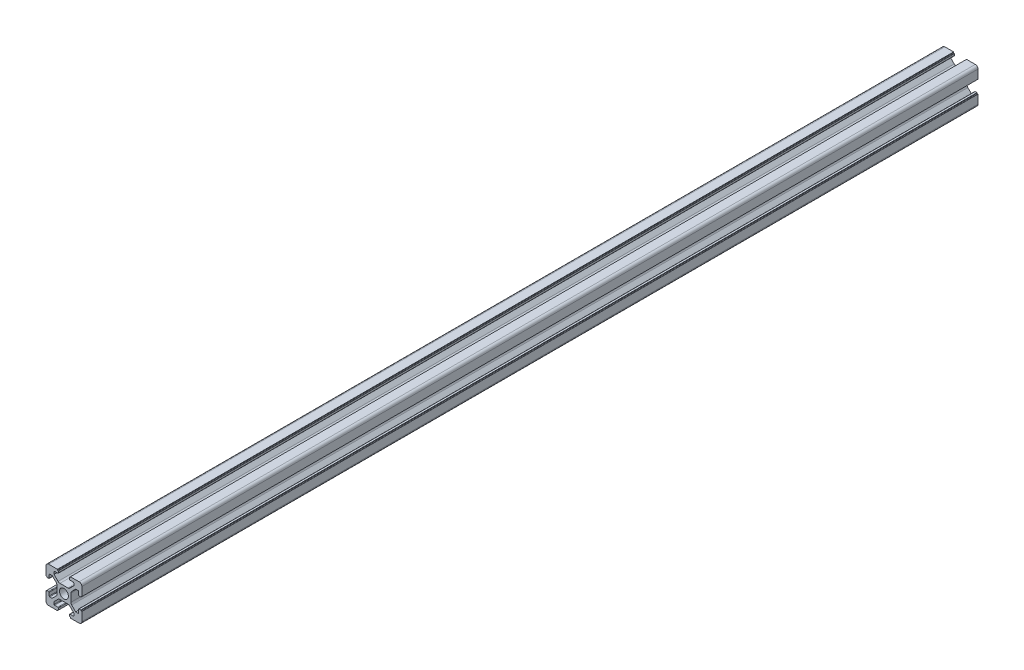
SolidWorks part; units mm, degrees
ref_plane "前视基准面" through (0, 0, 0) normal (0, 0, 1) x (1, 0, 0)
ref_plane "上视基准面" through (0, 0, 0) normal (0, 1, 0) x (1, 0, 0)
ref_plane "右视基准面" through (0, 0, 0) normal (1, 0, 0) x (0, 0, -1)
sketch "草图1" plane through (0, 0, 0) normal (0, 0, 1) x (1, 0, 0)
  line L0 (4.216, 3.2442) -> (6.4367, 5.4649)
  line L1 (6.4367, 5.4649) -> (7.7767, 5.4649)
  line L2 (8.0767, 5.1649) -> (8.0767, 3.3649)
  line L3 (8.3767, 3.0649) -> (9.3767, 3.0649)
  line L4 (9.3767, 3.0649) -> (9.3767, 3.3649)
  line L5 (9.5767, 3.5649) -> (9.8767, 3.5649)
  line L6 (9.8767, 3.5649) -> (9.8767, 8.4649)
  line L7 (8.3767, 9.9649) -> (3.4767, 9.9649)
  line L8 (3.4767, 9.9649) -> (3.4767, 9.6649)
  line L9 (3.2767, 9.4649) -> (2.9767, 9.4649)
  line L10 (2.9767, 9.4649) -> (2.9767, 8.4649)
  line L11 (3.2767, 8.1649) -> (5.0767, 8.1649)
  line L12 (5.3767, 7.8649) -> (5.3767, 6.5249)
  line L13 (5.3767, 6.5249) -> (3.156, 4.3042)
  line L14 (2.0953, 3.8649) -> (-2.342, 3.8649)
  line L15 (-3.4027, 4.3042) -> (-5.6233, 6.5249)
  line L16 (-5.6233, 6.5249) -> (-5.6233, 7.8649)
  line L17 (-5.3233, 8.1649) -> (-3.5233, 8.1649)
  line L18 (-3.2233, 8.4649) -> (-3.2233, 9.4649)
  line L19 (-3.2233, 9.4649) -> (-3.5233, 9.4649)
  line L20 (-3.7233, 9.6649) -> (-3.7233, 9.9649)
  line L21 (-3.7233, 9.9649) -> (-8.6233, 9.9649)
  line L22 (-10.1233, 8.4649) -> (-10.1233, 3.5649)
  line L23 (-10.1233, 3.5649) -> (-9.8233, 3.5649)
  line L24 (-9.6233, 3.3649) -> (-9.6233, 3.0649)
  line L25 (-9.6233, 3.0649) -> (-8.6233, 3.0649)
  line L26 (-8.3233, 3.3649) -> (-8.3233, 5.1649)
  line L27 (-8.0233, 5.4649) -> (-6.6833, 5.4649)
  line L28 (-6.6833, 5.4649) -> (-4.4627, 3.2442)
  line L29 (-4.0233, 2.1836) -> (-4.0233, -2.2538)
  line L30 (-4.4627, -3.3144) -> (-6.6833, -5.5351)
  line L31 (-6.6833, -5.5351) -> (-8.0233, -5.5351)
  line L32 (-8.3233, -5.2351) -> (-8.3233, -3.4351)
  line L33 (-8.6233, -3.1351) -> (-9.6233, -3.1351)
  line L34 (-9.6233, -3.1351) -> (-9.6233, -3.4351)
  line L35 (-9.8233, -3.6351) -> (-10.1233, -3.6351)
  line L36 (-10.1233, -3.6351) -> (-10.1233, -8.5351)
  line L37 (-8.6233, -10.0351) -> (-3.7233, -10.0351)
  line L38 (-3.7233, -10.0351) -> (-3.7233, -9.7351)
  line L39 (-3.5233, -9.5351) -> (-3.2233, -9.5351)
  line L40 (-3.2233, -9.5351) -> (-3.2233, -8.5351)
  line L41 (-3.5233, -8.2351) -> (-5.3233, -8.2351)
  line L42 (-5.6233, -7.9351) -> (-5.6233, -6.5951)
  line L43 (-5.6233, -6.5951) -> (-3.4027, -4.3744)
  line L44 (-2.342, -3.9351) -> (2.0953, -3.9351)
  line L45 (3.156, -4.3744) -> (5.3767, -6.5951)
  line L46 (5.3767, -6.5951) -> (5.3767, -7.9351)
  line L47 (5.0767, -8.2351) -> (3.2767, -8.2351)
  line L48 (2.9767, -8.5351) -> (2.9767, -9.5351)
  line L49 (2.9767, -9.5351) -> (3.2767, -9.5351)
  line L50 (3.4767, -9.7351) -> (3.4767, -10.0351)
  line L51 (3.4767, -10.0351) -> (8.3767, -10.0351)
  line L52 (9.8767, -8.5351) -> (9.8767, -3.6351)
  line L53 (9.8767, -3.6351) -> (9.5767, -3.6351)
  line L54 (9.3767, -3.4351) -> (9.3767, -3.1351)
  line L55 (9.3767, -3.1351) -> (8.3767, -3.1351)
  line L56 (8.0767, -3.4351) -> (8.0767, -5.2351)
  line L57 (7.7767, -5.5351) -> (6.4367, -5.5351)
  line L58 (6.4367, -5.5351) -> (4.216, -3.3144)
  line L59 (3.7767, -2.2538) -> (3.7767, 2.1836)
  circle A0 centre (-0.1233, -0.0351) radius 2.5
  arc A1 (8.0767, 5.1649) -> (7.7767, 5.4649) centre (7.7767, 5.1649) ccw
  arc A2 (8.0767, 3.3649) -> (8.3767, 3.0649) centre (8.3767, 3.3649) ccw
  arc A3 (9.5767, 3.5649) -> (9.3767, 3.3649) centre (9.5767, 3.3649) ccw
  arc A4 (9.8767, 8.4649) -> (8.3767, 9.9649) centre (8.3767, 8.4649) ccw
  arc A5 (3.2767, 9.4649) -> (3.4767, 9.6649) centre (3.2767, 9.6649) ccw
  arc A6 (2.9767, 8.4649) -> (3.2767, 8.1649) centre (3.2767, 8.4649) ccw
  arc A7 (5.3767, 7.8649) -> (5.0767, 8.1649) centre (5.0767, 7.8649) ccw
  arc A8 (2.0953, 3.8649) -> (3.156, 4.3042) centre (2.0953, 5.3649) ccw
  arc A9 (-3.4027, 4.3042) -> (-2.342, 3.8649) centre (-2.342, 5.3649) ccw
  arc A10 (-5.3233, 8.1649) -> (-5.6233, 7.8649) centre (-5.3233, 7.8649) ccw
  arc A11 (-3.5233, 8.1649) -> (-3.2233, 8.4649) centre (-3.5233, 8.4649) ccw
  arc A12 (-3.7233, 9.6649) -> (-3.5233, 9.4649) centre (-3.5233, 9.6649) ccw
  arc A13 (-8.6233, 9.9649) -> (-10.1233, 8.4649) centre (-8.6233, 8.4649) ccw
  arc A14 (-9.6233, 3.3649) -> (-9.8233, 3.5649) centre (-9.8233, 3.3649) ccw
  arc A15 (-8.6233, 3.0649) -> (-8.3233, 3.3649) centre (-8.6233, 3.3649) ccw
  arc A16 (-8.0233, 5.4649) -> (-8.3233, 5.1649) centre (-8.0233, 5.1649) ccw
  arc A17 (-4.0233, 2.1836) -> (-4.4627, 3.2442) centre (-5.5233, 2.1836) ccw
  arc A18 (-4.4627, -3.3144) -> (-4.0233, -2.2538) centre (-5.5233, -2.2538) ccw
  arc A19 (-8.3233, -5.2351) -> (-8.0233, -5.5351) centre (-8.0233, -5.2351) ccw
  arc A20 (-8.3233, -3.4351) -> (-8.6233, -3.1351) centre (-8.6233, -3.4351) ccw
  arc A21 (-9.8233, -3.6351) -> (-9.6233, -3.4351) centre (-9.8233, -3.4351) ccw
  arc A22 (-10.1233, -8.5351) -> (-8.6233, -10.0351) centre (-8.6233, -8.5351) ccw
  arc A23 (-3.5233, -9.5351) -> (-3.7233, -9.7351) centre (-3.5233, -9.7351) ccw
  arc A24 (-3.2233, -8.5351) -> (-3.5233, -8.2351) centre (-3.5233, -8.5351) ccw
  arc A25 (-5.6233, -7.9351) -> (-5.3233, -8.2351) centre (-5.3233, -7.9351) ccw
  arc A26 (-2.342, -3.9351) -> (-3.4027, -4.3744) centre (-2.342, -5.4351) ccw
  arc A27 (3.156, -4.3744) -> (2.0953, -3.9351) centre (2.0953, -5.4351) ccw
  arc A28 (5.0767, -8.2351) -> (5.3767, -7.9351) centre (5.0767, -7.9351) ccw
  arc A29 (3.2767, -8.2351) -> (2.9767, -8.5351) centre (3.2767, -8.5351) ccw
  arc A30 (3.4767, -9.7351) -> (3.2767, -9.5351) centre (3.2767, -9.7351) ccw
  arc A31 (8.3767, -10.0351) -> (9.8767, -8.5351) centre (8.3767, -8.5351) ccw
  arc A32 (9.3767, -3.4351) -> (9.5767, -3.6351) centre (9.5767, -3.4351) ccw
  arc A33 (8.3767, -3.1351) -> (8.0767, -3.4351) centre (8.3767, -3.4351) ccw
  arc A34 (7.7767, -5.5351) -> (8.0767, -5.2351) centre (7.7767, -5.2351) ccw
  arc A35 (3.7767, -2.2538) -> (4.216, -3.3144) centre (5.2767, -2.2538) ccw
  arc A36 (4.216, 3.2442) -> (3.7767, 2.1836) centre (5.2767, 2.1836) ccw
extrude "凸台-拉伸1" add sketch "草图1" along normal blind 500
